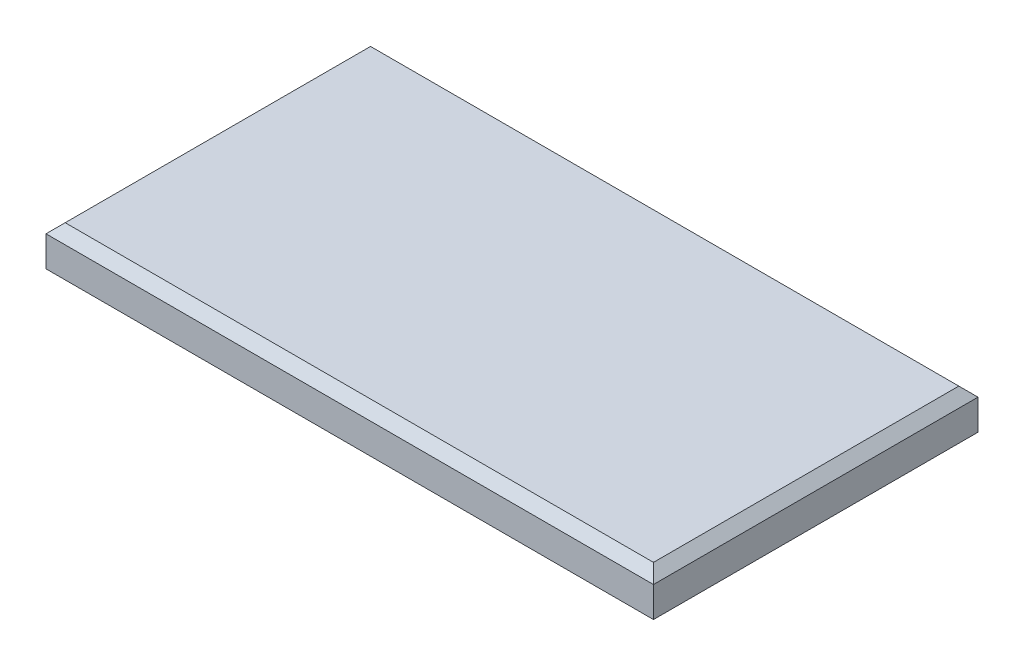
SolidWorks part; units mm, degrees
material "Mahogany"
ref_plane "Front Plane" through (0, 0, 0) normal (0, 0, 1) x (1, 0, 0)
ref_plane "Top Plane" through (0, 0, 0) normal (0, 1, 0) x (1, 0, 0)
ref_plane "Right Plane" through (0, 0, 0) normal (1, 0, 0) x (0, 0, -1)
sketch "Sketch1" plane through (0, 0, 0) normal (0, 1, 0) x (1, 0, 0)
  line L1 (190, 101.5) -> (-190, 101.5)
  line L2 (190, 101.5) -> (190, -101.5)
  line L3 (190, -101.5) -> (-190, -101.5)
  line L4 (-190, 101.5) -> (-190, -101.5)
  line L5 (190, 101.5) -> (-190, -101.5) construction
  line L6 (190, -101.5) -> (-190, 101.5) construction
  point P0 (0, 0)
  dimension "D1" = 380
  dimension "D2" = 203
extrude "Boss-Extrude1" add sketch "Sketch1" along normal blind 25
chamfer "Chamfer1" distance 6 angle 45 4 edges at (0, 25, -101.5) (190, 25, 0) (0, 25, 101.5) (-190, 25, 0)
